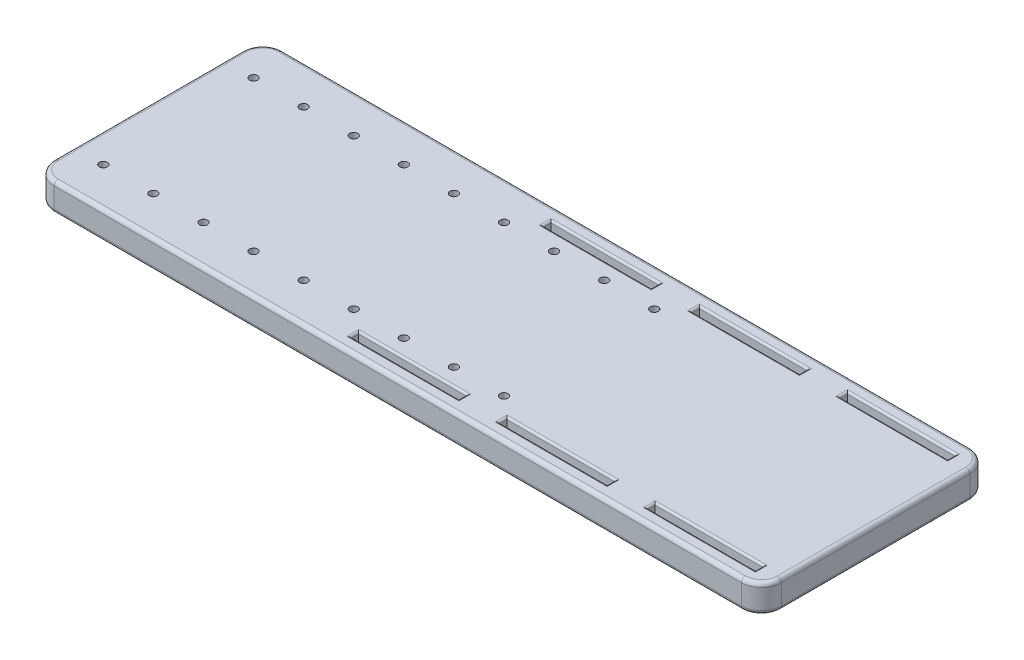
SolidWorks part; units mm, degrees
ref_plane "Front" through (0, 0, 0) normal (0, 0, 1) x (1, 0, 0)
ref_plane "Top" through (0, 0, 0) normal (0, 1, 0) x (1, 0, 0)
ref_plane "Right" through (0, 0, 0) normal (1, 0, 0) x (0, 0, -1)
sketch "Sketch6" plane through (0, 0, 0) normal (0, 0, 1) x (1, 0, 0)
  line L1 (-90.75, 3.5) -> (90.75, 3.5)
  line L2 (-90.75, 3.5) -> (-90.75, -3.5)
  line L3 (-90.75, -3.5) -> (90.75, -3.5)
  line L4 (90.75, 3.5) -> (90.75, -3.5)
  line L5 (-90.75, 3.5) -> (90.75, -3.5) construction
  line L6 (-90.75, -3.5) -> (90.75, 3.5) construction
  point P0 (0, 0)
  dimension "D2" = 7
  dimension "D1" = 181.5
extrude "Boss-Extrude2" add sketch "Sketch6" along normal mid plane 57
sketch "Sketch2" plane through (0, 3.5, 24.5) normal (0, -1, 0) x (1, 0, 0)
  line L0 (-90.75, -0.5) -> (90.75, -0.5) construction
  line L1 (35.25, -48.5) -> (35.25, -0.5) construction
  line L2 (72.25, -48.5) -> (72.25, -0.5) construction
  line L3 (-1.75, -0.5) -> (-1.75, -48.5) construction
  line L4 (-15.25, 0.5) -> (11.75, 0.5)
  line L5 (-15.25, 0.5) -> (-15.25, -1.5)
  line L6 (-15.25, -1.5) -> (11.75, -1.5)
  line L7 (11.75, 0.5) -> (11.75, -1.5)
  line L8 (-15.25, 0.5) -> (11.75, -1.5) construction
  line L9 (-15.25, -1.5) -> (11.75, 0.5) construction
  line L10 (21.75, 0.5) -> (48.75, 0.5)
  line L11 (21.75, 0.5) -> (21.75, -1.5)
  line L12 (21.75, -1.5) -> (48.75, -1.5)
  line L13 (48.75, 0.5) -> (48.75, -1.5)
  line L14 (21.75, 0.5) -> (48.75, -1.5) construction
  line L15 (21.75, -1.5) -> (48.75, 0.5) construction
  line L16 (58.75, 0.5) -> (85.75, 0.5)
  line L17 (58.75, 0.5) -> (58.75, -1.5)
  line L18 (58.75, -1.5) -> (85.75, -1.5)
  line L19 (85.75, 0.5) -> (85.75, -1.5)
  line L20 (58.75, 0.5) -> (85.75, -1.5) construction
  line L21 (58.75, -1.5) -> (85.75, 0.5) construction
  line L24 (-90.75, 4) -> (-90.75, -53) construction
  line L25 (90.75, 4) -> (90.75, -53) construction
  line L26 (90.75, 4) -> (-90.75, 4) construction
  line L27 (-90.75, -48.5) -> (90.75, -48.5) construction
  line L28 (90.75, -53) -> (-90.75, -53) construction
  line L30 (-15.25, -49.5) -> (11.75, -49.5)
  line L31 (-15.25, -49.5) -> (-15.25, -47.5)
  line L32 (-15.25, -47.5) -> (11.75, -47.5)
  line L33 (11.75, -49.5) -> (11.75, -47.5)
  line L34 (-15.25, -49.5) -> (11.75, -47.5) construction
  line L35 (-15.25, -47.5) -> (11.75, -49.5) construction
  line L36 (21.75, -49.5) -> (48.75, -49.5)
  line L37 (21.75, -49.5) -> (21.75, -47.5)
  line L38 (21.75, -47.5) -> (48.75, -47.5)
  line L39 (48.75, -49.5) -> (48.75, -47.5)
  line L40 (21.75, -49.5) -> (48.75, -47.5) construction
  line L41 (21.75, -47.5) -> (48.75, -49.5) construction
  line L42 (58.75, -49.5) -> (85.75, -49.5)
  line L43 (58.75, -49.5) -> (58.75, -47.5)
  line L44 (58.75, -47.5) -> (85.75, -47.5)
  line L45 (85.75, -49.5) -> (85.75, -47.5)
  line L46 (58.75, -49.5) -> (85.75, -47.5) construction
  line L47 (58.75, -47.5) -> (85.75, -49.5) construction
  point P5 (-1.75, -48.5)
  point P6 (-1.75, -0.5)
  point P11 (35.25, -0.5)
  point P16 (72.25, -0.5)
  point P32 (35.25, -48.5)
  point P37 (72.25, -48.5)
  dimension "D1" = 2
  dimension "D2" = 27
  dimension "D3" = 4.5
  dimension "D4" = 10
  dimension "D5" = 10
  dimension "D6" = 5
  dimension "D7" = 4.5
extrude "Cut-Extrude1" cut sketch "Sketch2" along normal up to surface (7 mm away) up to face at (0, -3.5, 0)
sketch "Sketch3" plane through (0, 3.5, 0) normal (0, 1, 0) x (1, 0, 0)
  line L0 (-90.75, 0) -> (90.75, 0) construction
  line L2 (16.75, 18.75) -> (16.75, -18.75) construction
  line L6 (11.75, -24) -> (21.75, -24) construction
  line L8 (21.75, -25) -> (21.75, -23) construction
  line L9 (-90.75, -28.5) -> (-90.75, 28.5) construction
  line L10 (90.75, -28.5) -> (90.75, 28.5) construction
  line L11 (11.75, -23) -> (11.75, -25) construction
  circle A2 centre (16.75, 18.75) radius 1
  circle A3 centre (16.75, -18.75) radius 1
  point P0 (25, 0)
  point P7 (16.75, 0)
  point P20 (16.75, -24)
  dimension "D3" = 2
  dimension "D1" = 37.5
extrude "Cut-Extrude2" cut sketch "Sketch3" against normal through all
sketch "Sketch4" plane through (0, -3.5, 0) normal (0, -1, 0) x (1, 0, 0)
  circle A0 centre (16.75, -18.75) radius 2
  circle A1 centre (16.75, 18.75) radius 2
  dimension "D1" = 4
extrude "Cut-Extrude3" cut sketch "Sketch4" against normal blind 1.75
fillet "Fillet5" radius 0.5 2 edges at (16.75, -3.5, -20.75) (16.75, -3.5, 16.75)
pattern_linear "LPattern1" count 9 spacing 12.5 along (-1, 0, 0) of "Cut-Extrude2", "Cut-Extrude3", "Fillet5"
fillet "Fillet2" radius 0.5 48 edges at (21.75, 3.5, 24) (35.25, 3.5, 25) (48.75, 3.5, 24) (35.25, 3.5, 23) (85.75, -3.5, 24) (72.25, -3.5, 25) (58.75, -3.5, 24) (72.25, -3.5, 23) (48.75, -3.5, 24) (35.25, -3.5, 25) (21.75, -3.5, 24) (35.25, -3.5, 23) (48.75, -3.5, -24) (35.25, -3.5, -23) (21.75, -3.5, -24) (35.25, -3.5, -25) (85.75, -3.5, -24) (72.25, -3.5, -23) (58.75, -3.5, -24) (72.25, -3.5, -25) (21.75, 3.5, -24) (35.25, 3.5, -23) (48.75, 3.5, -24) (35.25, 3.5, -25) (58.75, 3.5, -24) (72.25, 3.5, -23) (85.75, 3.5, -24) (72.25, 3.5, -25) (58.75, 3.5, 24) (72.25, 3.5, 25) (85.75, 3.5, 24) (72.25, 3.5, 23) (-15.25, 3.5, -24) (-1.75, 3.5, -23) (11.75, 3.5, -24) (-1.75, 3.5, -25) (-15.25, 3.5, 24) (-1.75, 3.5, 25) (11.75, 3.5, 24) (-1.75, 3.5, 23) (11.75, -3.5, 24) (-1.75, -3.5, 25) (-15.25, -3.5, 24) (-1.75, -3.5, 23) (11.75, -3.5, -24) (-1.75, -3.5, -23) (-15.25, -3.5, -24) (-1.75, -3.5, -25)
fillet "Fillet6" radius 5 4 edges at (90.75, 0, -28.5) (90.75, 0, 28.5) (-90.75, 0, -28.5) (-90.75, 0, 28.5)
fillet "Fillet7" radius 1 16 edges at (-89.2855, -3.5, 27.0355) (-90.75, -3.5, 0) (-89.2855, -3.5, -27.0355) (0, -3.5, -28.5) (89.2855, -3.5, -27.0355) (90.75, -3.5, 0) (89.2855, -3.5, 27.0355) (89.2855, 3.5, 27.0355) (90.75, 3.5, 0) (89.2855, 3.5, -27.0355) (0, 3.5, -28.5) (-89.2855, 3.5, -27.0355) (-90.75, 3.5, 0) (-89.2855, 3.5, 27.0355) (0, -3.5, 28.5) (0, 3.5, 28.5)
sketch "Sketch5" plane through (0, -3.5, 0) normal (0, -1, 0) x (1, 0, 0)
  line L0 (90.75, -2.5) -> (0, -2.5) construction
  line L3 (0, 0) -> (90.75, 0) construction
  line L4 (90.75, 28.5) -> (90.75, -28.5) construction
  text T0 "KM-MB40-5-A" font "Calibri" height 5
  dimension "D1" = 2.5
extrude "Part Number Cut" cut sketch "Sketch5" against normal blind 0.6
equation "\"Screw Hole Spacing\"= 12.5mm"
equation "\"D3@LPattern1\"=\"Screw Hole Spacing\""
equation "\"D1@Sketch3\"=\"Screw Hole Spacing\"*3"
equation "\"Screw Hole Qty\"= 9"
equation "\"D1@LPattern1\"=\"Screw Hole Qty\""
equation "\"D1@Sketch6\"=69+\"Screw Hole Spacing\"*\"Screw Hole Qty\""
